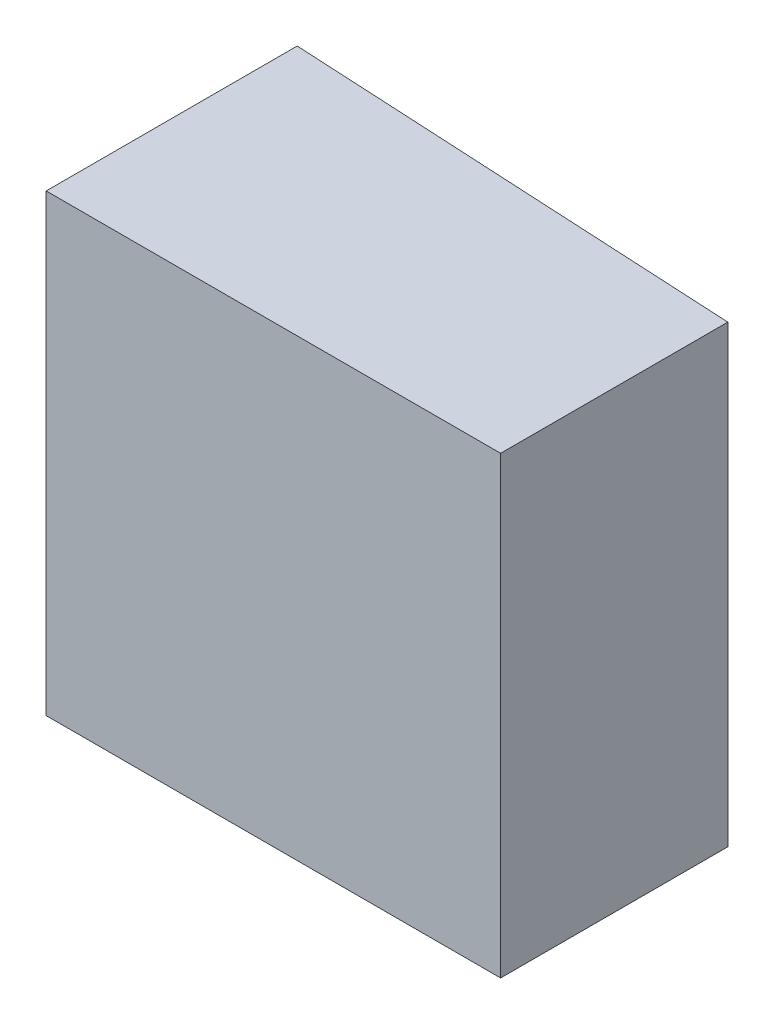
SolidWorks part; units mm, degrees
ref_plane "前视基准面" through (0, 0, 0) normal (0, 0, 1) x (1, 0, 0)
ref_plane "上视基准面" through (0, 0, 0) normal (0, 1, 0) x (1, 0, 0)
ref_plane "右视基准面" through (0, 0, 0) normal (1, 0, 0) x (0, 0, -1)
other "Configuration Table"
sketch "草图1" plane through (0, 0, 0) normal (0, 0, 1) x (1, 0, 0)
  line L1 (0, 0) -> (20, 0)
  line L2 (0, 0) -> (0, 20)
  line L3 (0, 20) -> (20, 20)
  line L4 (20, 0) -> (20, 20)
extrude "BaseBox" add sketch "草图1" along normal blind 10
draft "Draft3deg" type of draft neutral plane draft angle 3 faces to draft 1 face at (10, 10, 0) neutral plane through (20, 0, 10) neutral plane normal (1, 0, 0) parameters "D1"=3
